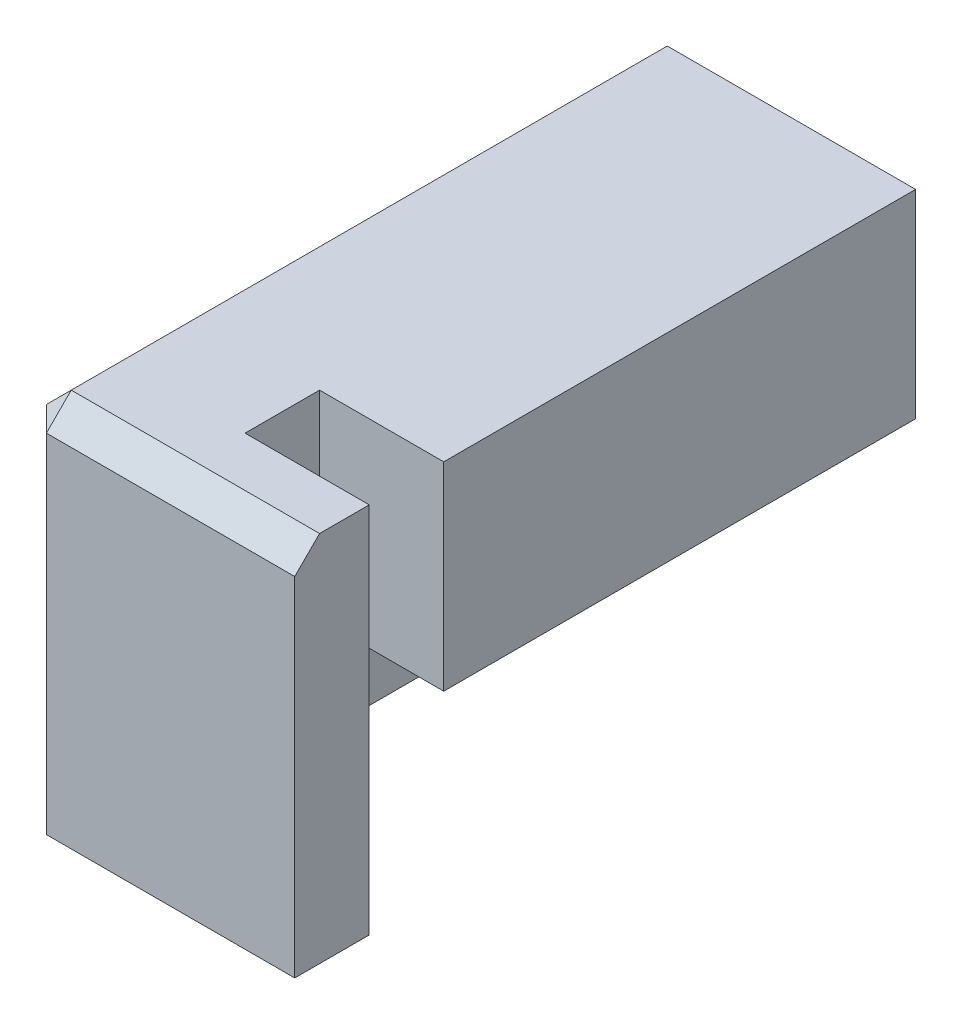
SolidWorks part; units mm, degrees
ref_plane "Front Plane" through (0, 0, 0) normal (0, 0, 1) x (1, 0, 0)
ref_plane "Top Plane" through (0, 0, 0) normal (0, 1, 0) x (1, 0, 0)
ref_plane "Right Plane" through (0, 0, 0) normal (1, 0, 0) x (0, 0, -1)
sketch "Sketch1" plane through (0, 0, 0) normal (0, 1, 0) x (1, 0, 0)
  line L0 (0, 0) -> (5, 0)
  line L1 (5, 0) -> (5, 19)
  line L2 (5, 19) -> (-6, 19)
  line L3 (-6, 19) -> (-6, -6)
  line L4 (-6, -6) -> (5, -6)
  line L5 (5, -6) -> (5, -3)
  line L6 (5, -3) -> (0, -3)
  line L7 (0, -3) -> (0, 0)
  dimension "D1" = 11
  dimension "D2" = 5
  dimension "D3" = 3
  dimension "D4" = 25
  dimension "D5" = 5
  dimension "D6" = 3
extrude "Boss-Extrude1" add sketch "Sketch1" along normal blind 15
sketch "Sketch2" plane through (0, 0, 0) normal (0, -1, 0) x (1, 0, 0)
  line L1 (-3, -38.8223) -> (0, -38.8223)
  line L2 (-3, -38.8223) -> (-3, 3)
  line L3 (-3, 3) -> (0, 3)
  line L4 (0, -38.8223) -> (0, 3)
  line L5 (-3, -38.8223) -> (0, 3) construction
  line L6 (-3, 3) -> (0, -38.8223) construction
  point P0 (-1.5, -17.9112)
  dimension "D1" = 3
extrude "Cut-Extrude1" cut sketch "Sketch2" against normal offset from surface (12 mm away) 3 up to face at (1, 15, -2.5)
chamfer "Chamfer1" distance 1 angle 45 3 edges at (-6, 7.5, 6) (-0.5, 15, 6) (-6, 15, -6.5)
sketch "Sketch3" plane through (0, 0, -19) normal (0, 0, -1) x (-1, 0, 0)
  line L0 (3, 12) -> (0, 12) construction
  line L1 (-5.6961, -4.0312) -> (0, -4.0312)
  line L2 (-5.6961, -4.0312) -> (-5.6961, 7)
  line L3 (-5.6961, 7) -> (0, 7)
  line L4 (0, -4.0312) -> (0, 7)
  line L5 (-5.6961, -4.0312) -> (0, 7) construction
  line L6 (-5.6961, 7) -> (0, -4.0312) construction
  line L7 (0, 0) -> (0, 12) construction
  point P0 (-2.8481, 1.4844)
  dimension "D1" = 5
extrude "Cut-Extrude2" cut sketch "Sketch3" against normal up to surface (22 mm away) up to face at (0.6667, 9, 3)
